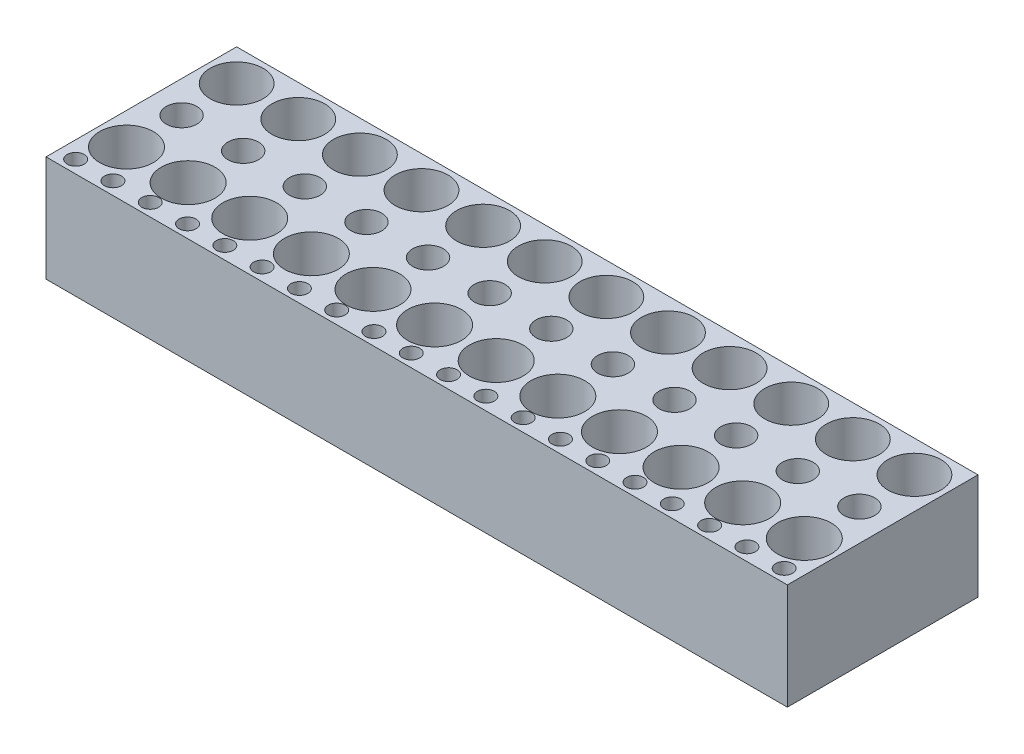
SolidWorks part; units mm, degrees
ref_plane "前视基准面" through (0, 0, 0) normal (0, 0, 1) x (1, 0, 0)
ref_plane "上视基准面" through (0, 0, 0) normal (0, 1, 0) x (1, 0, 0)
ref_plane "右视基准面" through (0, 0, 0) normal (1, 0, 0) x (0, 0, -1)
other "Configuration Table"
sketch "草图1" plane through (0, 0, 0) normal (0, 1, 0) x (1, 0, 0)
  line L1 (-17.5, 4.5) -> (17.5, 4.5)
  line L2 (-17.5, 4.5) -> (-17.5, -4.5)
  line L3 (-17.5, -4.5) -> (17.5, -4.5)
  line L4 (17.5, 4.5) -> (17.5, -4.5)
  line L5 (-17.5, 4.5) -> (17.5, -4.5) construction
  line L6 (-17.5, -4.5) -> (17.5, 4.5) construction
  point P0 (0, 0)
  dimension "D1" = 35
  dimension "D2" = 9
extrude "凸台-拉伸1" add sketch "草图1" along normal blind 5
sketch "草图2" plane through (0, 5, 0) normal (0, 1, 0) x (1, 0, 0)
  line L0 (17.5, 4.5) -> (-17.5, 4.5) construction
  line L1 (-17.5, 4.5) -> (-17.5, -4.5) construction
  line L2 (17.5, -4.5) -> (17.5, 4.5) construction
  line L3 (-17.5, -4.5) -> (17.5, -4.5) construction
  circle A0 centre (-16, 3) radius 1.25
  circle A1 centre (-13.0909, 3) radius 1.25
  circle A2 centre (-10.1818, 3) radius 1.25
  circle A3 centre (-7.2727, 3) radius 1.25
  circle A4 centre (-4.3636, 3) radius 1.25
  circle A5 centre (-1.4545, 3) radius 1.25
  circle A6 centre (1.4545, 3) radius 1.25
  circle A7 centre (4.3636, 3) radius 1.25
  circle A8 centre (7.2727, 3) radius 1.25
  circle A9 centre (10.1818, 3) radius 1.25
  circle A10 centre (13.0909, 3) radius 1.25
  circle A11 centre (16, 3) radius 1.25
  circle A12 centre (-16, 0.4) radius 0.725
  circle A13 centre (-13.0909, 0.4) radius 0.725
  circle A14 centre (-10.1818, 0.4) radius 0.725
  circle A15 centre (-7.2727, 0.4) radius 0.725
  circle A16 centre (-4.3636, 0.4) radius 0.725
  circle A17 centre (-1.4545, 0.4) radius 0.725
  circle A18 centre (1.4545, 0.4) radius 0.725
  circle A19 centre (4.3636, 0.4) radius 0.725
  circle A20 centre (7.2727, 0.4) radius 0.725
  circle A21 centre (10.1818, 0.4) radius 0.725
  circle A22 centre (13.0909, 0.4) radius 0.725
  circle A23 centre (16, 0.4) radius 0.725
  circle A24 centre (-16, -2.2) radius 1.27
  circle A25 centre (-13.0909, -2.2) radius 1.27
  circle A26 centre (-10.1818, -2.2) radius 1.27
  circle A27 centre (-7.2727, -2.2) radius 1.27
  circle A28 centre (-4.3636, -2.2) radius 1.27
  circle A29 centre (-1.4545, -2.2) radius 1.27
  circle A30 centre (1.4545, -2.2) radius 1.27
  circle A31 centre (4.3636, -2.2) radius 1.27
  circle A32 centre (7.2727, -2.2) radius 1.27
  circle A33 centre (10.1818, -2.2) radius 1.27
  circle A34 centre (13.0909, -2.2) radius 1.27
  circle A35 centre (16, -2.2) radius 1.27
  circle A36 centre (-16.7, -3.9) radius 0.4
  circle A37 centre (-14.9395, -3.9) radius 0.4
  circle A38 centre (-13.1789, -3.9) radius 0.4
  circle A39 centre (-11.4184, -3.9) radius 0.4
  circle A40 centre (-9.6579, -3.9) radius 0.4
  circle A41 centre (-7.8974, -3.9) radius 0.4
  circle A42 centre (-6.1368, -3.9) radius 0.4
  circle A43 centre (-4.3763, -3.9) radius 0.4
  circle A44 centre (-2.6158, -3.9) radius 0.4
  circle A45 centre (-0.8553, -3.9) radius 0.4
  circle A46 centre (0.9053, -3.9) radius 0.4
  circle A47 centre (2.6658, -3.9) radius 0.4
  circle A48 centre (4.4263, -3.9) radius 0.4
  circle A49 centre (6.1868, -3.9) radius 0.4
  circle A50 centre (7.9474, -3.9) radius 0.4
  circle A51 centre (9.7079, -3.9) radius 0.4
  circle A52 centre (11.4684, -3.9) radius 0.4
  circle A53 centre (13.2289, -3.9) radius 0.4
  circle A54 centre (14.9895, -3.9) radius 0.4
  circle A55 centre (16.75, -3.9) radius 0.4
  dimension "D1" = 2.5
  dimension "D5" = 1.45
  dimension "D9" = 2.54
  dimension "D12" = 0.8
  dimension "D2" = 1.5
  dimension "D3" = 1.5
  dimension "D4" = 1.5
  dimension "D6" = 2.6
  dimension "D7" = 1.5
  dimension "D8" = 2.6
  dimension "D10" = 1.5
  dimension "D11" = 0.6
  dimension "D13" = 0.8
  dimension "D14" = 0.75
extrude "切除-拉伸1" cut sketch "草图2" against normal blind 5
